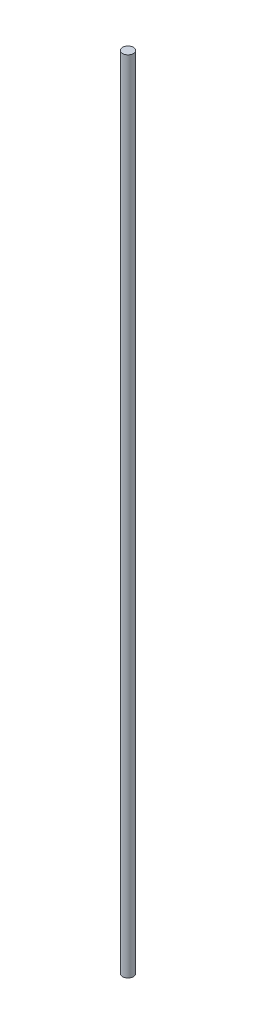
SolidWorks part; units mm, degrees
ref_plane "Front Plane" through (0, 0, 0) normal (0, 0, 1) x (1, 0, 0)
ref_plane "Top Plane" through (0, 0, 0) normal (0, 1, 0) x (1, 0, 0)
ref_plane "Right Plane" through (0, 0, 0) normal (1, 0, 0) x (0, 0, -1)
sketch "Sketch1" plane through (0, 0, 0) normal (0, 1, 0) x (1, 0, 0)
  circle A0 centre (0, 0) radius 6.35
  dimension "D1" = 12.7
extrude "Boss-Extrude1" add sketch "Sketch1" along normal blind 935.5
